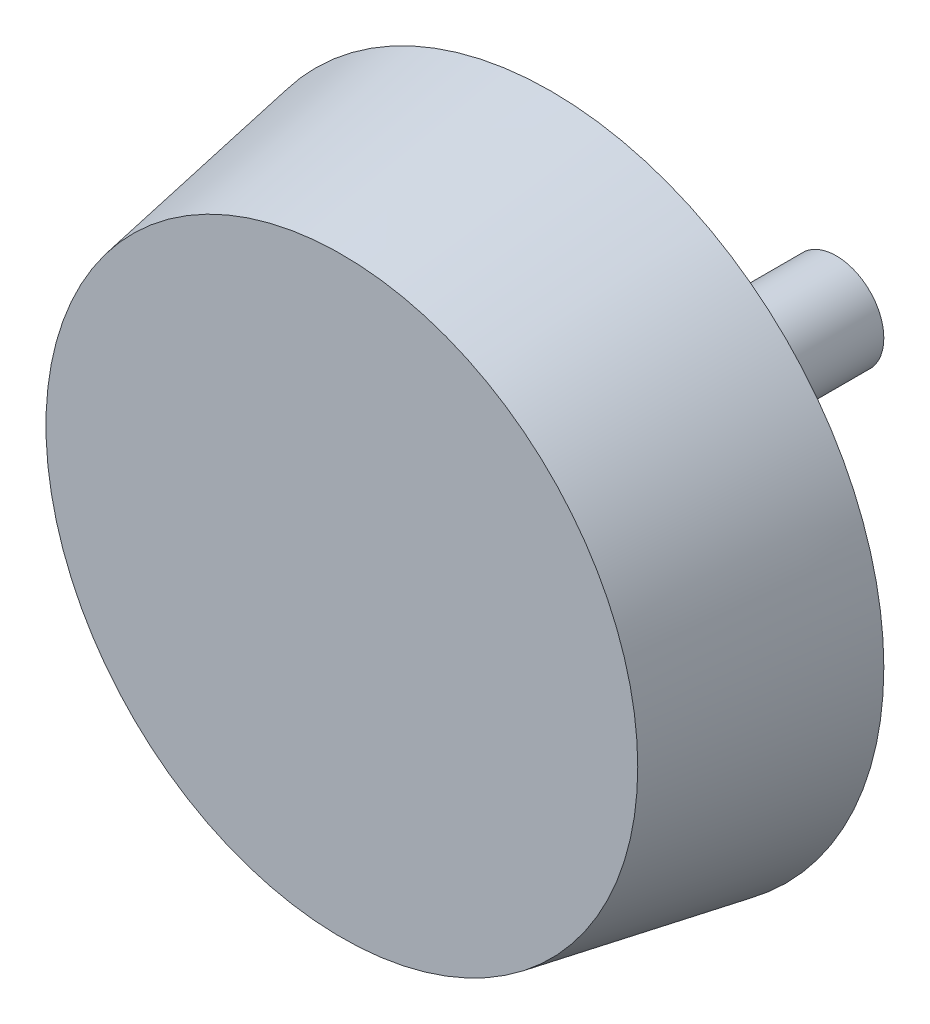
SolidWorks part; units mm, degrees
ref_plane "Спереди" through (0, 0, 0) normal (0, 0, 1) x (1, 0, 0)
ref_plane "Сверху" through (0, 0, 0) normal (0, 1, 0) x (1, 0, 0)
ref_plane "Справа" through (0, 0, 0) normal (1, 0, 0) x (0, 0, -1)
sketch "Эскиз2" plane through (0, 0, 0) normal (0, 0, 1) x (1, 0, 0)
  circle A0 centre (0, 0) radius 35
  dimension "D1" = 70
extrude "Бобышка-Вытянуть1" add sketch "Эскиз2" along normal blind 22 draft 10
sketch "Эскиз3" plane through (0, 0, 0) normal (0, 0, -1) x (-1, 0, 0)
  circle A0 centre (0, 0) radius 5
  dimension "D1" = 10
extrude "Бобышка-Вытянуть2" add sketch "Эскиз3" along normal blind 30
